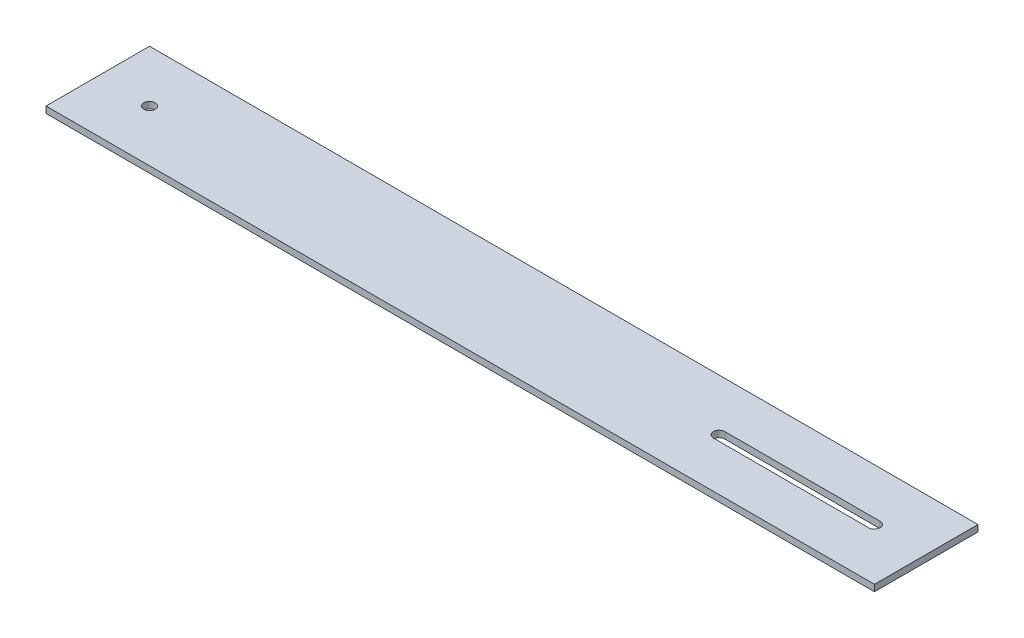
SolidWorks part; units mm, degrees
ref_plane "Front Plane" through (0, 0, 0) normal (0, 0, 1) x (1, 0, 0)
ref_plane "Top Plane" through (0, 0, 0) normal (0, 1, 0) x (1, 0, 0)
ref_plane "Right Plane" through (0, 0, 0) normal (1, 0, 0) x (0, 0, -1)
sketch "Sketch1" plane through (0, 0, 0) normal (0, 1, 0) x (1, 0, 0)
  line L0 (304.8, 28.1781) -> (381, 28.1781)
  line L1 (0, 0) -> (406.4, 0)
  line L2 (0, 0) -> (0, 50.8)
  line L3 (0, 50.8) -> (406.4, 50.8)
  line L4 (406.4, 0) -> (406.4, 50.8)
  line L5 (304.8, 22.6219) -> (381, 22.6219)
  circle A0 centre (25.4, 25.4) radius 2.7781
  arc A1 (304.8, 28.1781) -> (304.8, 22.6219) centre (304.8, 25.4) ccw
  arc A2 (381, 22.6219) -> (381, 28.1781) centre (381, 25.4) ccw
  dimension "D5" = 5.5562
  dimension "D8" = 5.5562
  dimension "D9" = 5.5562
  dimension "D1" = 406.4
  dimension "D2" = 50.8
  dimension "D3" = 25.4
  dimension "D4" = 25.4
  dimension "D6" = 25.4
  dimension "D7" = 76.2
  dimension "D10" = 25.4
extrude "Boss-Extrude1" add sketch "Sketch1" along normal blind 3.175
